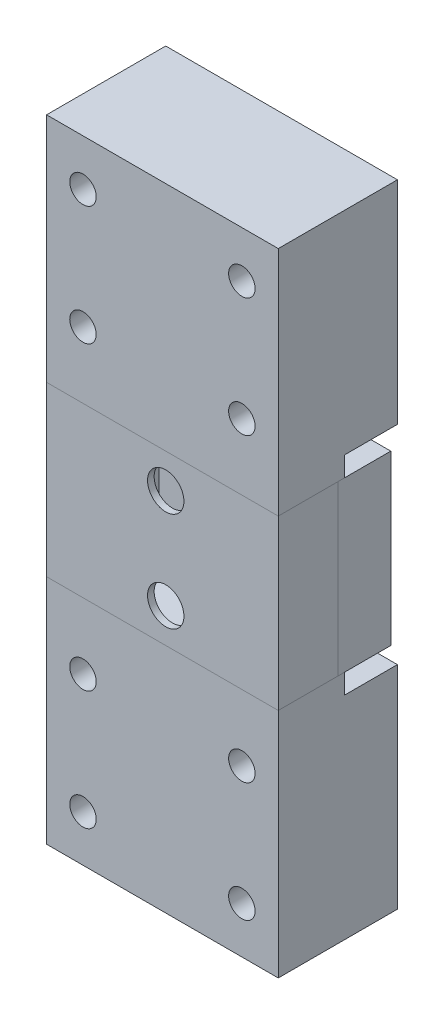
SolidWorks part; units mm, degrees
ref_plane "Front Plane" through (0, 0, 0) normal (0, 0, 1) x (1, 0, 0)
ref_plane "Top Plane" through (0, 0, 0) normal (0, 1, 0) x (1, 0, 0)
ref_plane "Right Plane" through (0, 0, 0) normal (1, 0, 0) x (0, 0, -1)
sketch "Sketch1" plane through (0, 0, 0) normal (0, 0, 1) x (1, 0, 0)
  line L5 (237, 0) -> (237, 25.4292)
  line L6 (200, 0) -> (200, -2)
  line L7 (200, 25.4292) -> (200, 27.4292)
  line L8 (200, 0) -> (237, 0)
  line L9 (237, 25.4292) -> (200, 25.4292)
  circle A4 centre (195.1014, 5.2292) radius 2.75
  circle A5 centre (195.1014, 20.2292) radius 2.75
  circle A6 centre (219.5, 5.2292) radius 2.75
  circle A7 centre (219.5, 20.2292) radius 2.75
sketch "Sketch2" plane through (0, 0, 0) normal (0, 0, 1) x (1, 0, 0)
  line L0 (200, 0) -> (237, 0) construction
  line L1 (237, 25.4292) -> (202, 25.4292)
  line L2 (237, 25.4292) -> (237, 0)
  line L3 (237, 0) -> (202, 0)
  line L4 (202, 25.4292) -> (202, 0)
  line L5 (219.5, 0) -> (219.5, 25.4292) construction
  line L6 (220, 25.4292) -> (220, 0) construction
  line L7 (202, 12.7146) -> (237, 12.7146) construction
  circle A4 centre (220, 5.2) radius 2.75
  circle A5 centre (220, 20.2292) radius 2.75
  dimension "D2" = 5.5
  dimension "D1" = 0.5
  dimension "D3" = 5.2
extrude "Boss-Extrude1" add sketch "Sketch2" along normal blind 8
sketch "Sketch3" plane through (0, 0, 8) normal (0, 0, 1) x (1, 0, 0)
  line L0 (200, 0) -> (237, 0) construction
  line L1 (237, 25.4292) -> (229, 25.4292)
  line L2 (237, 25.4292) -> (237, 0)
  line L3 (237, 0) -> (229, 0)
  line L4 (229, 25.4292) -> (229, 0)
  line L5 (219.5, 25.4292) -> (219.5, 0) construction
  line L6 (237, 25.4292) -> (202, 25.4292) construction
  line L7 (210, 25.4292) -> (210, 0)
  line L8 (202, 0) -> (210, 0)
  line L9 (202, 25.4292) -> (202, 0)
  line L10 (202, 25.4292) -> (210, 25.4292)
  dimension "D1" = 8
extrude "Boss-Extrude2" add sketch "Sketch3" along normal blind 8 separate body
ref_plane "Plane1" through (0, 0, 12) normal (0, 0, 1) x (1, 0, 0)
mirror "Mirror1" about plane through (0, 0, 12) normal (0, 0, 1) of "Boss-Extrude1"
sketch "Sketch4" plane through (0, 25.4292, 0) normal (0, 1, 0) x (1, 0, 0)
  line L1 (237, -7) -> (202, -7)
  line L2 (237, -24) -> (202, -24) construction
  line L5 (237, -24) -> (202, -24)
  line L7 (202, -24) -> (202, -7)
  line L9 (237, -7) -> (237, -24)
  dimension "D1" = 17
extrude "Boss-Extrude3" add sketch "Sketch4" along normal blind 35 separate body
ref_plane "Plane2" through (219.5, 0, 0) normal (1, 0, 0) x (0, 0, -1)
sketch "Sketch5" plane through (0, 0, 7) normal (0, 0, -1) x (-1, 0, 0)
  line L0 (-237, 60.4292) -> (-202, 60.4292) construction
  line L1 (-237, 60.4292) -> (-202, 60.4292)
  line L2 (-237, 60.4292) -> (-237, 28.4292)
  line L3 (-237, 28.4292) -> (-202, 28.4292)
  line L4 (-202, 60.4292) -> (-202, 28.4292)
  line L5 (-202, 60.4292) -> (-202, 25.4292) construction
  dimension "D1" = 32
extrude "Boss-Extrude4" add sketch "Sketch5" along normal blind 8
ref_plane "Plane3" through (0, 12.7146, 0) normal (0, -1, 0) x (-1, 0, 0)
sketch "Sketch7" plane through (0, 0, -1) normal (0, 0, -1) x (-1, 0, 0)
  circle A4 centre (-231.5, 53.4292) radius 2
  circle A5 centre (-231.5, 35.4292) radius 2
  circle A6 centre (-207.5, 35.4292) radius 2
  circle A7 centre (-207.5, 53.4292) radius 2
extrude "Cut-Extrude2" cut sketch "Sketch7" against normal through all
mirror "Mirror2" about plane through (0, 12.7146, 0) normal (0, -1, 0) of bodies 112 106
sketch "Sketch6" plane through (0, 60.4292, 0) normal (0, 1, 0) x (1, 0, 0)
  line L0 (237, -24) -> (237, 1) construction
  line L1 (202, -24) -> (237, -24)
  line L2 (202, -24) -> (202, -17)
  line L3 (202, -17) -> (237, -17)
  line L4 (237, -24) -> (237, -17)
  dimension "D1" = 7
extrude "Cut-Extrude1" cut sketch "Sketch6" against normal through all
